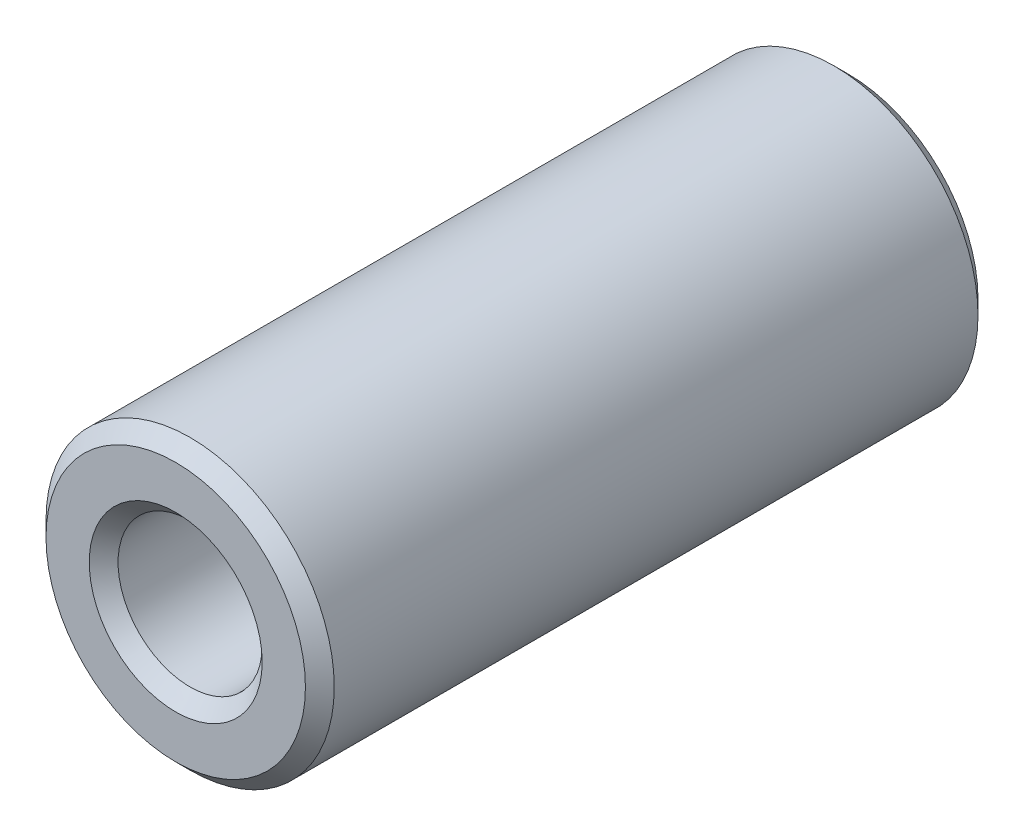
SolidWorks part; units mm, degrees
material "6061 合金"
ref_plane "正面" through (0, 0, 0) normal (0, 0, 1) x (1, 0, 0)
ref_plane "平面" through (0, 0, 0) normal (0, 1, 0) x (1, 0, 0)
ref_plane "右側面" through (0, 0, 0) normal (1, 0, 0) x (0, 0, -1)
sketch "ｽｹｯﾁ1" plane through (0, 0, 0) normal (0, 0, 1) x (1, 0, 0)
  circle A0 centre (0, 0) radius 3
  circle A1 centre (0, 0) radius 1.5
  dimension "D1" = 6
  dimension "D2" = 3
extrude "ﾎﾞｽ - 押し出し1" add sketch "ｽｹｯﾁ1" along normal blind 14
chamfer "面取り1" distance 0.3 4 edges at (1.5, 0, 0) (3, 0, 0) (1.5, 0, 14) (3, 0, 14)
